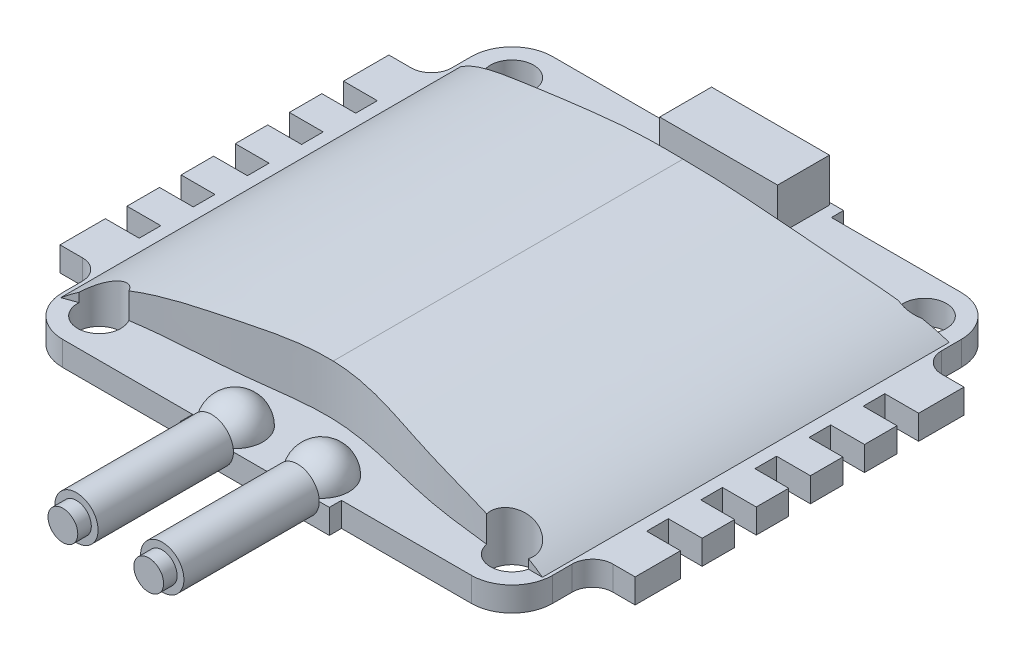
SolidWorks part; units mm, degrees
other "Caméra2"
ref_plane "Plan de face" through (0, 0, 0) normal (0, 0, 1) x (1, 0, 0)
ref_plane "Plan de dessus" through (0, 0, 0) normal (0, 1, 0) x (1, 0, 0)
ref_plane "Plan de droite" through (0, 0, 0) normal (1, 0, 0) x (0, 0, -1)
sketch "Esquisse1" plane through (0, 0, 0) normal (0, 1, 0) x (1, 0, 0)
  line L0 (-5.5, 18.1) -> (-5.5, 19)
  line L1 (15.1, -18.1) -> (5.5, -18.1)
  line L2 (18.1, -15.1) -> (18.1, -13.65)
  line L3 (15.1, 18.1) -> (5.5, 18.1)
  line L4 (-18.1, -15.1) -> (-18.1, -13.65)
  line L5 (18.1, -18.1) -> (-18.1, 18.1) construction
  line L6 (18.1, 18.1) -> (-18.1, -18.1) construction
  line L7 (-5.5, 19) -> (5.5, 19)
  line L8 (5.5, 19) -> (5.5, 18.1)
  line L9 (0, 19) -> (0, 0) construction
  line L10 (0, 0) -> (-21.25, 0) construction
  line L11 (5.5, -19) -> (5.5, -18.1)
  line L12 (-5.5, -19) -> (5.5, -19)
  line L13 (-5.5, -18.1) -> (-5.5, -19)
  line L14 (-5.5, 18.1) -> (-15.1, 18.1)
  line L15 (-5.5, -18.1) -> (-15.1, -18.1)
  line L16 (-19.6, 12.15) -> (-21.25, 12.15)
  line L17 (-21.25, 12.15) -> (-21.25, -12.15)
  line L18 (-21.25, -12.15) -> (-19.6, -12.15)
  line L19 (21.25, -12.15) -> (19.6, -12.15)
  line L20 (21.25, 12.15) -> (21.25, -12.15)
  line L21 (19.6, 12.15) -> (21.25, 12.15)
  line L22 (18.1, 13.65) -> (18.1, 15.1)
  line L23 (-18.1, 13.65) -> (-18.1, 15.1)
  arc A0 (15.1, -18.1) -> (18.1, -15.1) centre (15.1, -15.1) ccw
  arc A1 (-15.1, -18.1) -> (-18.1, -15.1) centre (-15.1, -15.1) cw
  arc A2 (-15.1, 18.1) -> (-18.1, 15.1) centre (-15.1, 15.1) ccw
  arc A3 (18.1, 15.1) -> (15.1, 18.1) centre (15.1, 15.1) ccw
  circle A4 centre (-15.25, 15.25) radius 1.6
  circle A5 centre (15.25, 15.25) radius 1.6
  circle A6 centre (15.25, -15.25) radius 1.6
  circle A7 centre (-15.25, -15.25) radius 1.6
  arc A8 (19.6, -12.15) -> (18.1, -13.65) centre (19.6, -13.65) ccw
  arc A9 (19.6, 12.15) -> (18.1, 13.65) centre (19.6, 13.65) cw
  arc A10 (-19.6, 12.15) -> (-18.1, 13.65) centre (-19.6, 13.65) ccw
  arc A11 (-19.6, -12.15) -> (-18.1, -13.65) centre (-19.6, -13.65) cw
  point P0 (0, 0)
  point P29 (0, 0)
  point P44 (-21.25, 0)
  point P52 (18.1, -12.15)
  point P55 (18.1, 12.15)
  point P58 (-18.1, 12.15)
  point P60 (-18.1, -12.15)
  dimension "D3" = 3
  dimension "D5" = 30.5
  dimension "D6" = 3.2
  dimension "D11" = 1.5
  dimension "D12" = 1.5
  dimension "D1" = 36.2
  dimension "D2" = 36.2
  dimension "D7" = 11
  dimension "D8" = 38
  dimension "D9" = 24.3
  dimension "D10" = 42.5
  dimension "D4" = 4
extrude "Boss.-Extru.1" add sketch "Esquisse1" along normal blind 1.8
sketch "Esquisse2" plane through (0, 1.8, 0) normal (0, 1, 0) x (1, 0, 0)
  line L0 (-21.25, 12.15) -> (-21.25, -12.15) construction
  line L1 (-21.25, 0.8) -> (-18.75, 0.8)
  line L2 (-21.25, 0.8) -> (-21.25, -0.8)
  line L3 (-21.25, -0.8) -> (-18.75, -0.8)
  line L4 (-18.75, 0.8) -> (-18.75, -0.8)
  line L5 (-18.75, 0) -> (0, 0) construction
  line L6 (-21.25, 4.8) -> (-18.75, 4.8)
  line L7 (-18.75, 4.8) -> (-18.75, 3.2)
  line L8 (-21.25, 3.2) -> (-18.75, 3.2)
  line L9 (-21.25, 4.8) -> (-21.25, 3.2)
  line L10 (-21.25, 8.8) -> (-18.75, 8.8)
  line L11 (-18.75, 8.8) -> (-18.75, 7.2)
  line L12 (-21.25, 7.2) -> (-18.75, 7.2)
  line L13 (-21.25, 8.8) -> (-21.25, 7.2)
  line L14 (-21.25, -3.2) -> (-18.75, -3.2)
  line L15 (-18.75, -3.2) -> (-18.75, -4.8)
  line L16 (-21.25, -4.8) -> (-18.75, -4.8)
  line L17 (-21.25, -3.2) -> (-21.25, -4.8)
  line L18 (-21.25, -7.2) -> (-18.75, -7.2)
  line L19 (-18.75, -7.2) -> (-18.75, -8.8)
  line L20 (-21.25, -8.8) -> (-18.75, -8.8)
  line L21 (-21.25, -7.2) -> (-21.25, -8.8)
  line L22 (0, 0) -> (0, 2.9127) construction
  line L23 (21.25, -7.2) -> (21.25, -8.8)
  line L24 (21.25, -8.8) -> (18.75, -8.8)
  line L25 (18.75, -7.2) -> (18.75, -8.8)
  line L26 (21.25, -7.2) -> (18.75, -7.2)
  line L27 (21.25, -3.2) -> (21.25, -4.8)
  line L28 (21.25, -4.8) -> (18.75, -4.8)
  line L29 (18.75, -3.2) -> (18.75, -4.8)
  line L30 (21.25, -3.2) -> (18.75, -3.2)
  line L31 (21.25, 8.8) -> (21.25, 7.2)
  line L32 (21.25, 7.2) -> (18.75, 7.2)
  line L33 (18.75, 8.8) -> (18.75, 7.2)
  line L34 (21.25, 8.8) -> (18.75, 8.8)
  line L35 (21.25, 4.8) -> (21.25, 3.2)
  line L36 (21.25, 3.2) -> (18.75, 3.2)
  line L37 (18.75, 4.8) -> (18.75, 3.2)
  line L38 (21.25, 4.8) -> (18.75, 4.8)
  line L39 (18.75, 0.8) -> (18.75, -0.8)
  line L40 (21.25, -0.8) -> (18.75, -0.8)
  line L41 (21.25, 0.8) -> (21.25, -0.8)
  line L42 (21.25, 0.8) -> (18.75, 0.8)
  dimension "D3" = 1.6
  dimension "D4" = 37.5
  dimension "D1" = 3
  dimension "D2" = 3
extrude "Enlèv. mat.-Extru.1" cut sketch "Esquisse2" against normal blind 2
sketch "Esquisse3" plane through (0, 1.8, 0) normal (0, 1, 0) x (1, 0, 0)
  line L0 (-3.1868, -15.2207) -> (-3.1868, -19.3201)
  arc A0 (-3.1868, -15.2207) -> (-3.1868, -19.3201) centre (-3.1868, -17.2704) ccw
revolve "Révolution1" add sketch "Esquisse3" angle 360 about L0
mirror "Symétrie1" about plane through (0, 0, 0) normal (1, 0, 0) of "Révolution1"
sketch "Esquisse4" plane through (0, 0, 19) normal (0, 0, 1) x (1, 0, 0)
  circle A0 centre (-3.1868, 1.8) radius 1.6
  circle A1 centre (3.1551, 1.8) radius 1.6
  dimension "D1" = 3.2
extrude "Boss.-Extru.2" add sketch "Esquisse4" along normal blind 10
sketch "Esquisse5" plane through (0, 0, 29) normal (0, 0, 1) x (1, 0, 0)
  circle A2 centre (-3.1868, 1.8) radius 1.1
  circle A3 centre (-3.1868, 1.8) radius 1.1
  circle A5 centre (3.1551, 1.8) radius 1.1
  circle A6 centre (3.1551, 1.8) radius 1.1
  dimension "D1" = 0.5
  dimension "D2" = 0.5
extrude "Boss.-Extru.3" add sketch "Esquisse5" along normal blind 1
sketch "Esquisse6" plane through (0, 1.8, 0) normal (0, 1, 0) x (1, 0, 0)
  line L1 (-4.0753, 18.8204) -> (4.6372, 18.8204)
  line L2 (-4.0753, 18.8204) -> (-4.0753, 14.9863)
  line L3 (-4.0753, 14.9863) -> (4.6372, 14.9863)
  line L4 (4.6372, 18.8204) -> (4.6372, 14.9863)
extrude "Boss.-Extru.4" add sketch "Esquisse6" along normal blind 3.2
sketch "Esquisse7" plane through (0, 0, -18.8204) normal (0, 0, -1) x (-1, 0, 0)
  line L0 (-0.281, 5) -> (-0.281, 2.9687) construction
  line L1 (-4.6372, 5) -> (4.0753, 5) construction
  line L2 (3.4657, 4.7088) -> (-4.0276, 4.7088)
  line L3 (-4.0276, 4.7088) -> (-4.0276, 4.2889)
  line L4 (-4.0276, 4.2889) -> (-4.2726, 4.2889)
  line L5 (-4.2726, 4.2889) -> (-4.2726, 3.8339)
  line L6 (-4.2726, 3.8339) -> (-4.0276, 3.8339)
  line L7 (-4.0276, 3.8339) -> (-4.0276, 2.1425)
  line L8 (-4.0276, 2.1425) -> (3.4657, 2.1425)
  line L9 (3.4657, 3.8339) -> (3.4657, 2.1425)
  line L10 (3.7106, 3.8339) -> (3.4657, 3.8339)
  line L11 (3.7106, 4.2889) -> (3.7106, 3.8339)
  line L12 (3.4657, 4.2889) -> (3.7106, 4.2889)
  line L13 (3.4657, 4.7088) -> (3.4657, 4.2889)
  point P13 (-0.281, 2.1425)
  point P18 (-0.281, 4.7088)
extrude "Enlèv. mat.-Extru.2" cut sketch "Esquisse7" against normal blind 3.2
sketch "Esquisse9" plane through (0, 0, 0) normal (0, 0, 1) x (1, 0, 0)
  line L0 (0, 9.3345) -> (0, -5.2062) construction
  line L1 (0, 5.5186) -> (-2.1619, 5.5186) construction
  line L3 (5.5, 1.8) -> (-5.5, 1.8) construction
  line L4 (-15.1, 1.8) -> (-18.1, 1.8) construction
  line L5 (-17.8475, 1.8) -> (17.8475, 1.8)
  spline S0 degree 3 poles (0, 5.5186) (2.1617, 5.5186) (5.0298, 5.4037) (12.242, 4.3393) (16.2988, 2.9631) (17.8475, 1.8) knots 0 0 0 0 0.30877 0.708154 1 1 1 1
  spline S1 degree 3 poles (0, 5.5186) (-2.1617, 5.5186) (-5.0298, 5.4037) (-12.242, 4.3393) (-16.2988, 2.9631) (-17.8475, 1.8) knots 0 0 0 0 0.30877 0.708154 1 1 1 1
  point P11 (0, 1.8)
extrude "Boss.-Extru.5" add sketch "Esquisse9" along normal mid plane 31.2 separate body
sketch "Esquisse10" plane through (0, 1.8, 0) normal (0, 1, 0) x (1, 0, 0)
  line L0 (19.8079, 15.1189) -> (19.8079, 29.571)
  line L1 (19.8079, 29.571) -> (-30.1574, 26.4296)
  line L2 (-30.1574, 26.4296) -> (-20.679, 15.1189)
  line L3 (-19.8837, -16.5056) -> (-33.6129, -29.8014)
  line L4 (-33.6129, -29.8014) -> (42.1732, -39.147)
  line L5 (42.1732, -39.147) -> (21.5123, -16.9222)
  spline S0 degree 3 poles (-19.8837, -16.5056) (-15.5976, -13.9495) (-8.7917, -14.3696) (0.8852, -12.6166) (9.9791, -15.7143) (17.3097, -15.633) (21.5123, -16.9222) knots 0 0 0 0 0.334207 0.481345 0.690018 1 1 1 1
  spline S1 degree 3 poles (-20.679, 15.1189) (-15.3319, 12.747) (-1.6479, 12.8201) (12.0579, 12.232) (19.8079, 15.1189) knots 0 0 0 0 0.412003 1 1 1 1
extrude "Enlèv. mat.-Extru.3" cut sketch "Esquisse10" along normal blind 31.2
combine bodies "Combiner1" operation type add bodies to combine 110 108
sketch "Esquisse11" plane through (0, 0, 0) normal (0, -1, 0) x (1, 0, 0)
  circle A0 centre (15.25, -15.25) radius 1.6 construction
  circle A1 centre (-15.25, -15.25) radius 1.6 construction
  circle A2 centre (-15.25, 15.25) radius 1.6 construction
  circle A3 centre (15.25, 15.25) radius 1.6 construction
  circle A4 centre (15.25, -15.25) radius 1.6
  circle A5 centre (-15.25, -15.25) radius 1.6
  circle A6 centre (-15.25, 15.25) radius 1.6
  circle A7 centre (15.25, 15.25) radius 1.6
extrude "Enlèv. mat.-Extru.4" cut sketch "Esquisse11" against normal blind 31.2
sketch "Esquisse12" plane through (0, 0, 0) normal (0, -1, 0) x (1, 0, 0)
  line L1 (-6.7036, 13.3242) -> (-3.6359, 13.3242)
  line L2 (-6.7036, 13.3242) -> (-6.7036, 10.105)
  line L3 (-6.7036, 10.105) -> (-3.6359, 10.105)
  line L4 (-3.6359, 13.3242) -> (-3.6359, 10.105)
  line L5 (-7.9535, 7.7947) -> (-4.0904, 7.7947)
  line L6 (-7.9535, 7.7947) -> (-7.9535, 4.1967)
  line L7 (-7.9535, 4.1967) -> (-4.0904, 4.1967)
  line L8 (-4.0904, 7.7947) -> (-4.0904, 4.1967)
  line L9 (3.7495, 7.7947) -> (7.9535, 7.7947)
  line L10 (3.7495, 7.7947) -> (3.7495, 4.1967)
  line L11 (3.7495, 4.1967) -> (7.9535, 4.1967)
  line L12 (7.9535, 7.7947) -> (7.9535, 4.1967)
  line L13 (5.3781, 13.3242) -> (8.4458, 13.3242)
  line L14 (5.3781, 13.3242) -> (5.3781, 10.105)
  line L15 (5.3781, 10.105) -> (8.4458, 10.105)
  line L16 (8.4458, 13.3242) -> (8.4458, 10.105)
  line L17 (3.7495, -5.5747) -> (7.9535, -5.5747)
  line L18 (3.7495, -5.5747) -> (3.7495, -9.3621)
  line L19 (3.7495, -9.3621) -> (7.9535, -9.3621)
  line L20 (7.9535, -5.5747) -> (7.9535, -9.3621)
  line L21 (-7.9535, -5.8399) -> (-4.0904, -5.8399)
  line L22 (-7.9535, -5.8399) -> (-7.9535, -9.3621)
  line L23 (-7.9535, -9.3621) -> (-4.0904, -9.3621)
  line L24 (-4.0904, -5.8399) -> (-4.0904, -9.3621)
  line L25 (-8.5973, -11.5588) -> (-5.6053, -11.5588)
  line L26 (-8.5973, -11.5588) -> (-8.5973, -14.4372)
  line L27 (-8.5973, -14.4372) -> (-5.6053, -14.4372)
  line L28 (-5.6053, -11.5588) -> (-5.6053, -14.4372)
  line L29 (3.2571, -11.5588) -> (6.3249, -11.5588)
  line L30 (3.2571, -11.5588) -> (3.2571, -14.4372)
  line L31 (3.2571, -14.4372) -> (6.3249, -14.4372)
  line L32 (6.3249, -11.5588) -> (6.3249, -14.4372)
extrude "Boss.-Extru.6" add sketch "Esquisse12" along normal blind 1
sketch "Esquisse13" plane through (0, 0, 0) normal (0, -1, 0) x (1, 0, 0)
  line L1 (-9.9608, 9.2339) -> (-8.711, 9.2339)
  line L2 (-9.9608, 9.2339) -> (-9.9608, 6.9993)
  line L3 (-9.9608, 6.9993) -> (-8.711, 6.9993)
  line L4 (-8.711, 9.2339) -> (-8.711, 6.9993)
  line L5 (1.3256, 9.2339) -> (2.5754, 9.2339)
  line L6 (1.3256, 9.2339) -> (1.3256, 6.9993)
  line L7 (1.3256, 6.9993) -> (2.5754, 6.9993)
  line L8 (2.5754, 9.2339) -> (2.5754, 6.9993)
  line L9 (-3.4086, -9.0212) -> (-2.1209, -9.0212)
  line L10 (-3.4086, -9.0212) -> (-3.4086, -10.9528)
  line L11 (-3.4086, -10.9528) -> (-2.1209, -10.9528)
  line L12 (-2.1209, -9.0212) -> (-2.1209, -10.9528)
  line L13 (8.4837, -9.4379) -> (9.8093, -9.4379)
  line L14 (8.4837, -9.4379) -> (8.4837, -11.3315)
  line L15 (8.4837, -11.3315) -> (9.8093, -11.3315)
  line L16 (9.8093, -9.4379) -> (9.8093, -11.3315)
extrude "Boss.-Extru.7" add sketch "Esquisse13" along normal blind 1.4
